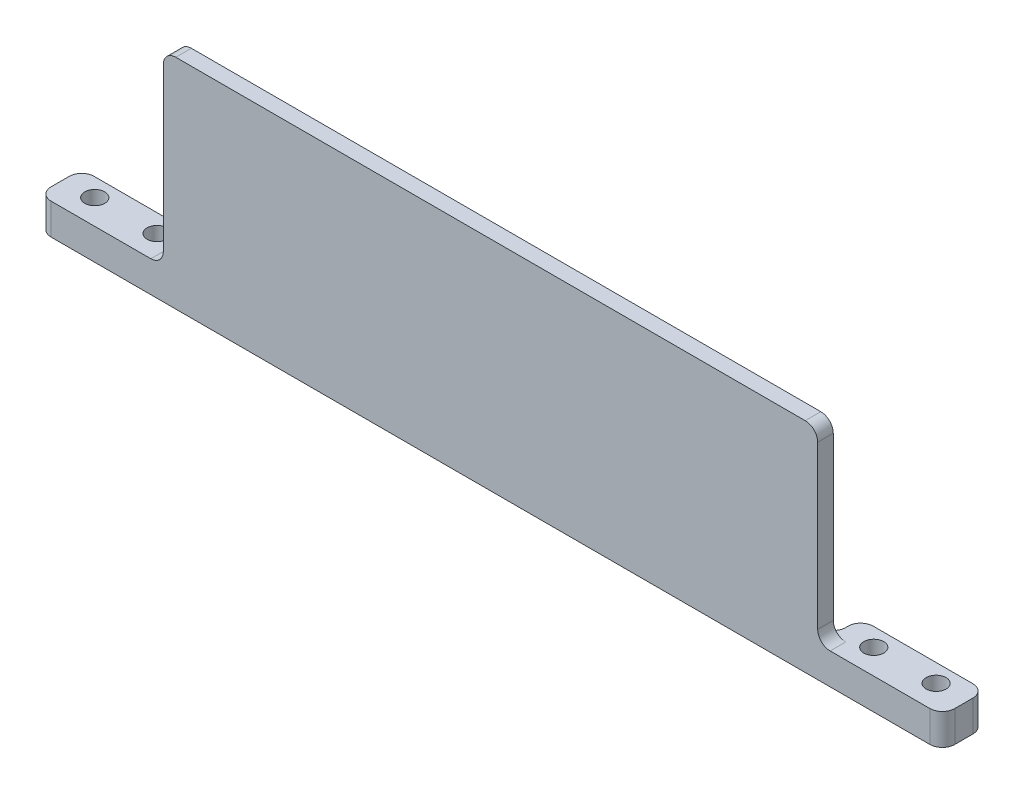
SolidWorks part; units mm, degrees
ref_plane "前视基准面" through (0, 0, 0) normal (0, 0, 1) x (1, 0, 0)
ref_plane "上视基准面" through (0, 0, 0) normal (0, 1, 0) x (1, 0, 0)
ref_plane "右视基准面" through (0, 0, 0) normal (1, 0, 0) x (0, 0, -1)
other "Configuration Table"
sketch "草图1" plane through (0, 0, 0) normal (0, 1, 0) x (1, 0, 0)
  line L0 (0, 0) -> (0, 65.3571) construction
  line L1 (0, 0) -> (-67.5, 0) construction
  line L2 (72.5, -4) -> (-72.5, -4)
  line L3 (72.5, -4) -> (72.5, 2.9)
  line L4 (52.5, 2.9) -> (52.5, -1.5)
  line L5 (-72.5, -4) -> (-72.5, 2.9)
  line L6 (-72.5, 2.9) -> (-52.5, 2.9)
  line L7 (-52.5, 2.9) -> (-52.5, -1.5)
  line L8 (-52.5, -1.5) -> (52.5, -1.5)
  line L9 (72.5, 2.9) -> (52.5, 2.9)
  circle A0 centre (-67.5, 0) radius 1.6
  circle A1 centre (-57.5, 0) radius 1.6
  circle A2 centre (67.5, 0) radius 1.6
  circle A3 centre (57.5, 0) radius 1.6
  point P19 (0, -4)
  point P21 (0, -1.5)
  dimension "D2" = 3.2
  dimension "D3" = 10
  dimension "D1" = 10
  dimension "D4" = 115
  dimension "D5" = 4
  dimension "D6" = 2.9
  dimension "D7" = 2.5
  dimension "D8" = 5
  dimension "D9" = 5
extrude "凸台-拉伸1" add sketch "草图1" along normal blind 5
sketch "草图2" plane through (0, 5, 0) normal (0, 1, 0) x (1, 0, 0)
  line L0 (-52.5, -1.5) -> (-52.5, -4)
  line L1 (-72.5, -4) -> (72.5, -4) construction
  line L2 (-52.5, -4) -> (52.5, -4)
  line L3 (52.5, -4) -> (52.5, -1.5)
  line L4 (52.5, -1.5) -> (-52.5, -1.5)
extrude "凸台-拉伸2" add sketch "草图2" along normal blind 30
fillet "圆角4" radius 2 10 edges at (-52.5, 35, 2.75) (52.5, 35, 2.75) (72.5, 2.5, -2.9) (52.5, 2.5, -2.9) (52.5, 2.5, 1.5) (-52.5, 2.5, 1.5) (-52.5, 2.5, -2.9) (-72.5, 2.5, -2.9) (-72.5, 2.5, 4) (72.5, 2.5, 4)
fillet "圆角5" radius 2 2 edges at (52.5, 5, 2.75) (-52.5, 5, 2.75)
